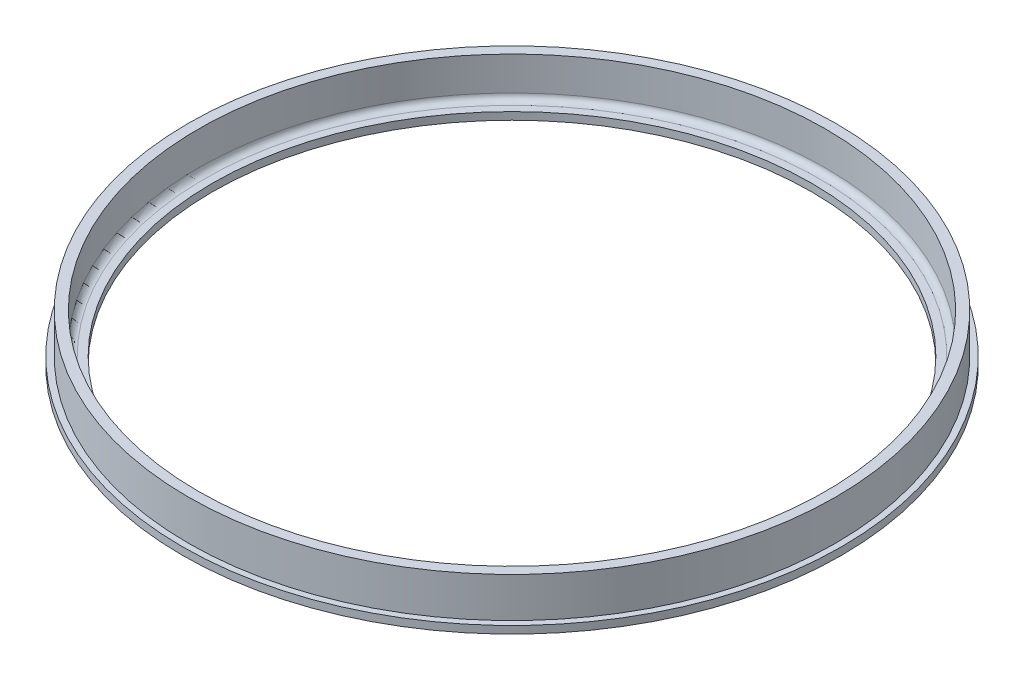
SolidWorks part; units mm, degrees
material "6061-T6 (SS)"
ref_plane "Front" through (0, 0, 0) normal (0, 0, 1) x (1, 0, 0)
ref_plane "Top" through (0, 0, 0) normal (0, 1, 0) x (1, 0, 0)
ref_plane "Right" through (0, 0, 0) normal (1, 0, 0) x (0, 0, -1)
sketch "Sketch1" plane through (0, 0, 0) normal (0, 0, 1) x (1, 0, 0)
  line L0 (0, 0) -> (0, 35.9551) construction
  line L1 (-83.82, -19.3305) -> (-83.82, -17.4255)
  line L2 (-83.82, -17.4255) -> (-82.296, -17.4255)
  line L3 (-76.2, -7.2655) -> (-76.2, -17.4255)
  line L4 (-82.296, -17.4255) -> (-82.296, -7.2655)
  line L5 (-76.2, -17.4255) -> (-76.2, -19.3305)
  line L6 (-76.2, -19.3305) -> (-83.82, -19.3305)
  line L7 (-76.2, -7.2655) -> (-82.296, -7.2655)
  dimension "D1" = 76.2
  dimension "D2" = 1.524
  dimension "D3" = 1.905
  dimension "D4" = 10.16
  dimension "D5" = 83.82
revolve "Revolve1" add sketch "Sketch1" angle 360 about L0
sketch "Sketch2" plane through (0, -7.2655, 0) normal (0, 1, 0) x (1, 0, 0)
  circle A0 centre (0, 0) radius 79.756
  circle A1 centre (0, 0) radius 82.296 construction
  circle A2 centre (0, 0) radius 82.296
  circle M2 centre (0, 0) radius 76.2
  dimension "D1" = 2.54
extrude "Cut-Extrude1" cut sketch "Sketch2" against normal blind 10.16 contours A0 M2
fillet "Fillet1" radius 1.5875 1 edges at (0, -17.4255, 79.756)
